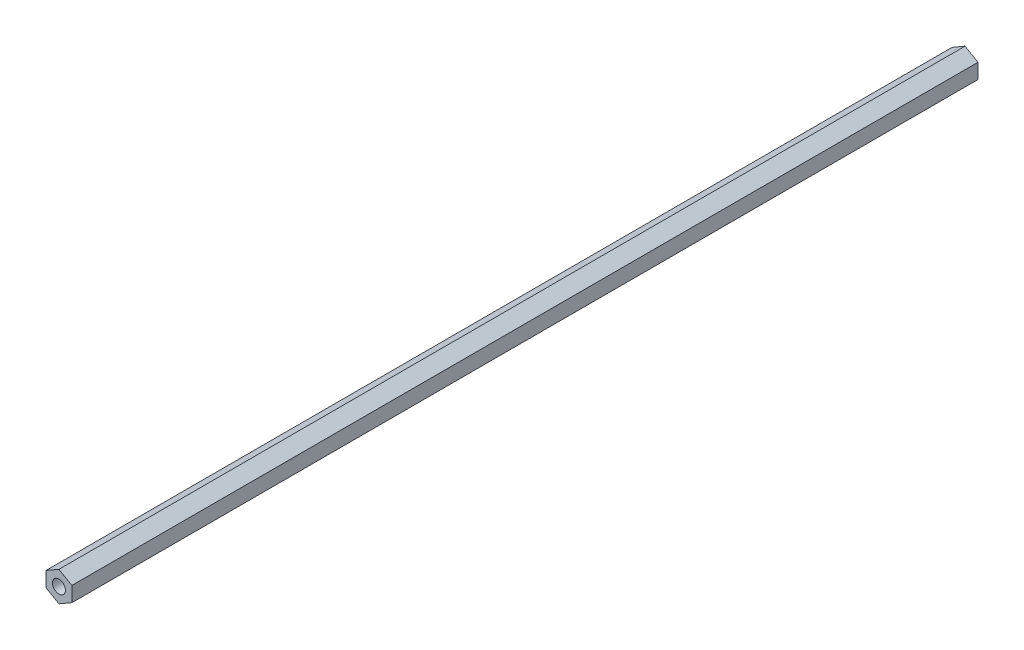
SolidWorks part; units mm, degrees
material "AISI 1020 Steel, Cold Rolled"
ref_plane "Front Plane" through (0, 0, 0) normal (0, 0, 1) x (1, 0, 0)
ref_plane "Top Plane" through (0, 0, 0) normal (0, 1, 0) x (1, 0, 0)
ref_plane "Right Plane" through (0, 0, 0) normal (1, 0, 0) x (0, 0, -1)
sketch "Sketch1" plane through (0, 0, 0) normal (0, 0, 1) x (1, 0, 0)
  line L1 (0, 7.3323) -> (-6.35, 3.6662) construction
  line L2 (-6.35, 3.6662) -> (-6.35, -3.6662) construction
  line L3 (-6.35, -3.6662) -> (0, -7.3323) construction
  line L4 (0, -7.3323) -> (6.35, -3.6662) construction
  line L5 (6.35, -3.6662) -> (6.35, 3.6662) construction
  line L6 (6.35, 3.6662) -> (0, 7.3323) construction
  circle A2 centre (0, 0) radius 6.35 construction
  dimension "Width" = 12.7
sketch "Sketch2" plane through (0, 0, 0) normal (1, 0, 0) x (0, 0, -1)
  line L0 (-222.25, 7.3323) -> (222.25, 7.3323) construction
  point P2 (0, 7.3323)
  point P3 (190.5, 7.3323)
  point P4 (-190.5, 7.3323)
  dimension "Length" = 444.5
  dimension "D2" = 31.75
  dimension "D1" = 31.75
sketch "Sketch3" plane through (0, 0, 0) normal (0, 0, 1) x (1, 0, 0)
  line L0 (-6.35, -3.6662) -> (0, -7.3323) construction
  line L1 (0, -7.3323) -> (6.35, -3.6662) construction
  line L2 (6.35, -3.6662) -> (6.35, 3.6662) construction
  line L3 (6.35, 3.6662) -> (0, 7.3323) construction
  line L4 (0, 7.3323) -> (-6.35, 3.6662) construction
  line L5 (-6.35, 3.6662) -> (-6.35, -3.6662) construction
  line L6 (-6.35, -3.6662) -> (0, -7.3323)
  line L7 (0, -7.3323) -> (6.35, -3.6662)
  line L8 (6.35, -3.6662) -> (6.35, 3.6662)
  line L9 (6.35, 3.6662) -> (0, 7.3323)
  line L10 (0, 7.3323) -> (-6.35, 3.6662)
  line L11 (-6.35, 3.6662) -> (-6.35, -3.6662)
extrude "Boss-Extrude2" add sketch "Sketch3" along normal up to vertex (222.25 mm away) and the other way up to vertex (222.25 mm away) up to point (0, 7.3323, 222.25) other way up to point (0, 7.3323, -222.25)
sketch "Sketch4" plane through (0, 0, 222.25) normal (0, 0, 1) x (1, 0, 0)
  point P0 (0, 0)
hole_wizard "1/4 (0.25) Diameter Hole1" positions "Sketch5" profile "Sketch6" hole size "1/4" standard "ANSI Inch"
sketch "Sketch5" plane through (0, 0, 222.25) normal (0, 0, 1) x (1, 0, 0)
  point P0 (0, 0)
sketch "Sketch6" plane through (0, 0, 222.25) normal (1, 0, 0) x (0, -1, 0)
  line L0 (0, 0) -> (0, 27.3077)
  line L1 (0, 27.3077) -> (3.175, 25.4)
  line L2 (3.175, 25.4) -> (3.175, 0)
  line L5 (3.175, 0) -> (0, 0)
  line L10 (0, 27.3077) -> (-3.175, 25.4) construction
  line L11 (0, -6.35) -> (0, 107.95) construction
  dimension "Hole Dia." = 6.35
  dimension "Hole Depth" = 25.4
  dimension "Drill Angle" = 118
hole_wizard "1/4 (0.25) Diameter Hole2" positions "Sketch7" profile "Sketch8" hole size "1/4" standard "ANSI Inch"
sketch "Sketch7" plane through (0, 0, -222.25) normal (0, 0, -1) x (-1, 0, 0)
  point P0 (0, 0)
sketch "Sketch8" plane through (0, 0, -222.25) normal (1, 0, 0) x (0, 1, 0)
  line L0 (0, 0) -> (0, 27.3077)
  line L1 (0, 27.3077) -> (3.175, 25.4)
  line L2 (3.175, 25.4) -> (3.175, 0)
  line L5 (3.175, 0) -> (0, 0)
  line L10 (0, 27.3077) -> (-3.175, 25.4) construction
  line L11 (0, -6.35) -> (0, 107.95) construction
  dimension "Hole Dia." = 6.35
  dimension "Hole Depth" = 25.4
  dimension "Drill Angle" = 118
equation "\"D2@Sketch2\" = \"D1@Sketch2\""
equation "\"D1@Sketch2\" = \"Width@Sketch1\" * 2.5"
